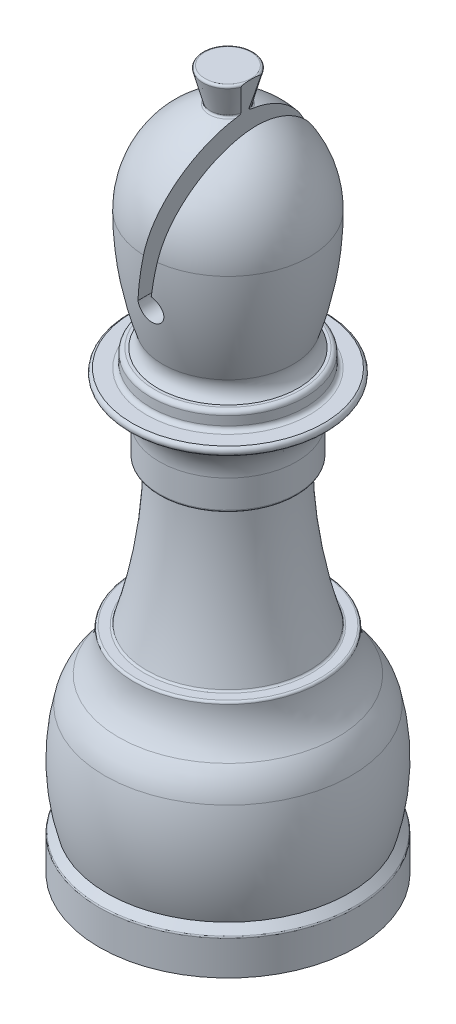
SolidWorks part; units mm, degrees
ref_plane "Front Plane" through (0, 0, 0) normal (0, 0, 1) x (1, 0, 0)
ref_plane "Top Plane" through (0, 0, 0) normal (0, 1, 0) x (1, 0, 0)
ref_plane "Right Plane" through (0, 0, 0) normal (1, 0, 0) x (0, 0, -1)
sketch "Sketch1" plane through (0, 0, 0) normal (0, 0, 1) x (1, 0, 0)
  line L0 (0, 81.5) -> (-2.6742, 81.5)
  line L1 (-15, 4) -> (-15, 0)
  line L2 (-14.1036, 5) -> (-14.9268, 4.1768)
  line L3 (-2.0398, 77.9166) -> (-2.9157, 81.1853)
  line L4 (-9, 51.4698) -> (-9, 52.5)
  line L5 (-8, 42.25) -> (-8, 45.5)
  line L6 (0, 81.5) -> (0, 0)
  line L7 (0, 0) -> (-15, 0)
  line L8 (-8.5, 53) -> (-8.1771, 53)
  line L9 (-9.5, 50.9698) -> (-11.1711, 50.9698)
  line L10 (-7.25, 42) -> (-7.75, 42)
  line L11 (-9.7092, 25) -> (-10.7092, 25)
  line L12 (0, 0) -> (0, -6.9862) construction
  line L13 (-2.9157, 81.1853) -> (-3, 81.5) construction
  line L14 (-3, 81.5) -> (-2.6742, 81.5) construction
  line L15 (-10.9592, 24.75) -> (-10.9592, 25.4702) construction
  arc A0 (-14.9268, 4.1768) -> (-15, 4) centre (-14.75, 4) ccw
  arc A1 (-14.3628, 16.9916) -> (-14.1036, 5) centre (9, 11.4981) ccw
  arc A3 (-10.7092, 25) -> (-10.9592, 24.75) centre (-10.7092, 24.75) ccw
  arc A4 (-9.7092, 25) -> (-9.4697, 25.1781) centre (-9.7092, 25.25) ccw
  arc A5 (-2.6742, 81.5) -> (-2.9157, 81.1853) centre (-2.6742, 81.25) ccw
  arc A6 (-2.1902, 77.6191) -> (-2.0398, 77.9166) centre (-2.2813, 77.8519) ccw
  arc A7 (-2.1902, 77.6191) -> (-9.5, 66.9097) centre (2, 66.9097) ccw
  arc A8 (-9.5, 66.9097) -> (-7.6013, 55.1283) centre (28, 66.9097) ccw
  arc A9 (-8.1771, 53) -> (-7.6013, 55.1283) centre (-9.5, 54.5) ccw
  arc A10 (-8.5, 53) -> (-9, 52.5) centre (-8.5, 52.5) ccw
  arc A11 (-9.5, 50.9698) -> (-9, 51.4698) centre (-9.5, 51.4698) ccw
  arc A12 (-11.1711, 50.9698) -> (-11.1711, 50.0302) centre (-11, 50.5) ccw
  arc A13 (-8, 45.5) -> (-11.1711, 50.0302) centre (-12.8214, 45.5) ccw
  arc A14 (-8, 42.25) -> (-7.75, 42) centre (-7.75, 42.25) ccw
  arc A15 (-7, 41.7489) -> (-7.25, 42) centre (-7.25, 41.75) ccw
  arc A16 (-9.4697, 25.1781) -> (-7, 41.7489) centre (-65.5114, 42) ccw
  arc A17 (-12.7539, 20.0697) -> (-10.9592, 24.75) centre (-17.9592, 24.75) ccw
  arc A18 (-12.7539, 20.0697) -> (-14.3628, 16.9916) centre (-7.5487, 15.3893) ccw
  dimension "D3" = 0.25
  dimension "D4" = 25
  dimension "D5" = 1
  dimension "D6" = 11.5
  dimension "D7" = 37.5
  dimension "D8" = 2
  dimension "D9" = 0.5
  dimension "D10" = 0.5
  dimension "D11" = 3
  dimension "D12" = 42
  dimension "D17" = 9.5
  dimension "D25" = 15
  dimension "D27" = 24
  dimension "D31" = 7
  dimension "D16" = 7
  dimension "D2" = 81.5
  dimension "D13" = 15
  dimension "D14" = 28
  dimension "D15" = 0.5
  dimension "D18" = 42
  dimension "D19" = 8
  dimension "D20" = 50.5
  dimension "D21" = 9
  dimension "D22" = 53
  dimension "D23" = 54.5
  dimension "D24" = 2
  dimension "D26" = 3
  dimension "D28" = 5
  dimension "D29" = 45.5
  dimension "D30" = 135
  dimension "D32" = 4
revolve "Revolve1" add sketch "Sketch1" angle 360 about L12
sketch "Sketch2" plane through (0, 0, 0) normal (0, 0, 1) x (1, 0, 0)
  line L0 (0.9164, 65.6538) -> (0.3439, 62.9601)
  line L1 (-1.5, 61.5) -> (-0.5901, 65.7807)
  line L2 (3.3474, 77.0908) -> (0.9164, 65.6538)
  line L3 (-0.5901, 65.7807) -> (1.9459, 77.7115)
  line L4 (1.9459, 77.7115) -> (2.7775, 81.6241)
  line L5 (2.7775, 81.6241) -> (4.2447, 81.3123)
  line L6 (4.2447, 81.3123) -> (3.3474, 77.0908)
  line L7 (0, 61.1245) -> (0, 78.4799) construction
  line L8 (0, 61.5) -> (0, 81.5) construction
  line L9 (0, 61.5) -> (0, 0) construction
  arc A0 (-1.5, 61.5) -> (0.3439, 62.9601) centre (0, 61.5) ccw
  arc A1 (9.5, 66.9097) -> (2.1902, 77.6191) centre (-2, 66.9097) ccw construction
  point P6 (0, 81.5)
  dimension "D2" = 1.5
  dimension "D1" = 12
  dimension "D3" = 20
  dimension "D4" = 1.5
  dimension "D5" = 61.5
  dimension "D6" = 4
extrude "Cut-Extrude1" cut sketch "Sketch2" against normal through all both and the other way through all
scale "Scale1" scale about origin uniform scaling yes scale factor 0.766667
sketch "Sketch3" plane through (0, 0, 0) normal (0, -1, 0) x (1, 0, 0)
  circle A0 centre (0, 0) radius 10.2
  dimension "D1" = 20.4
extrude "Cut-Extrude2" cut sketch "Sketch3" against normal blind 11 and the other way through all
sketch "Sketch4" plane through (0, 0, 0) normal (0, -1, 0) x (1, 0, 0)
  circle A0 centre (0, 0) radius 9.15
  circle A1 centre (0, 0) radius 10.2 construction
  circle A2 centre (0, 0) radius 10.2
  dimension "D1" = 18.3
sketch "Sketch5" plane through (0, 0, 0) normal (0, 0, 1) x (1, 0, 0)
  line L0 (10.8127, 3.8333) -> (10.8127, 14.5602) construction
  line L1 (10.8127, 3.8333) -> (-10.8127, 3.8333) construction
sketch "Sketch6" plane through (0, 0, 0) normal (0, 0, 1) x (1, 0, 0)
  line L0 (-10.75, 1) -> (0, 1)
  line L1 (-10.75, 1) -> (-10.75, 0)
  line L2 (-10.75, 0) -> (0, 0)
  line L3 (0, 0) -> (0, -1) construction
  line L4 (0, 0) -> (0, 1)
  point P0 (5.375, 0.75)
  point P4 (-6.925, 0)
  dimension "D1" = 12.3
  dimension "D2" = 1
  dimension "D3" = 3.825
  dimension "D4" = 21.5
revolve "Cut-Revolve1" cut sketch "Sketch6" angle 360 about L3
sketch "Sketch7" plane through (0, 0, 0) normal (0, 0, 1) x (1, 0, 0)
  line L0 (0, 0) -> (0, -0.9422) construction
  line L1 (0, 1.0046) -> (0, 3.5)
  line L2 (0, 3.5) -> (-10, 3.5)
  line L3 (-10.55, 0) -> (0, 0)
  line L4 (-10.55, 1) -> (-10.55, 0)
  line L5 (-10, 1) -> (-10.55, 1)
  line L6 (0, 0) -> (0, 1.0046)
  line L7 (-10, 1) -> (-10, 3.5)
  line L8 (-10.75, 0) -> (10.75, 0) construction
  dimension "D1" = 3.5
  dimension "D2" = 20
  dimension "D3" = 21.1
  dimension "D4" = 1
revolve "Base (Black Bishop)" add sketch "Sketch7" angle 360 about L0
sketch "Sketch8" [suppressed] plane through (0, 0, 0) normal (0, 0, 1) x (1, 0, 0)
  line L0 (0, 0) -> (0, -2.2211) construction
  line L1 (0, 0) -> (0, 4.5)
  line L2 (0, 4.5) -> (-10, 4.5)
  line L3 (-10.55, 0) -> (0, 0)
  line L4 (-10.55, 1) -> (-10.55, 0)
  line L5 (-10, 1) -> (-10.55, 1)
  line L7 (-10, 1) -> (-10, 4.5)
  dimension "D2" = 20
  dimension "D3" = 1
  dimension "D4" = 21.1
  dimension "D1" = 4.5
revolve "Base (White Bishop)" [suppressed] add sketch "Sketch8" angle 360 about L0
equation "\"D1@Sketch3\"=20.4mm"
equation "\"D1@Cut-Extrude2\"=5mm + 6mm"
equation "\"D1@Sketch4\"=\"WeightOuterDiam\"+0.3mm"
equation "\"D1\"= \"WeightHeight\""
equation "\"D1@Cut-Extrude3\"=\"QueenHeight\"+\"MagThickness\"-\"FeltThickness\""
equation "\"D1@Sketch2\"=\"MagDiam\""
equation "\"D1@Cut-Extrude1\"=\"QueenHeight\"+\"MagThickness\""
equation "\"MagDiam\"= 12mm"
equation "\"D1@Sketch6\"=\"MagDiam\"+0.3"
equation "\"D1@Sketch7\"=3.5mm"
equation "\"D1@Cut-Extrude4\"=\"SocketDepth\""
equation "\"D1@Sketch8\"=4.5mm"
equation "\"D1@Cut-Extrude5\"=\"ThreadedDepth\"+3mm"
equation "\"PawnHeight\"= 1mm"
equation "\"MagThickness\"= 3mm"
equation "\"KnightHeight\"= 2.5mm"
equation "\"RookHeight\"= 4mm"
equation "\"BishopHeight\"= 5.5mm"
equation "\"QueenHeight\"= 6.5mm"
equation "\"KingHeight\"= 8mm"
equation "\"WeightOuterDiam\"= 18mm"
equation "\"WeightInnerDiam\"= \"MagDiam\" + 0.3mm"
equation "\"WeightHeight\"= 9mm"
equation "\"BaseOuterDiam\"= 20mm"
equation "\"BaseInnerDiam\"= 12.7mm"
equation "\"FeltThickness\"= 1mm"
equation "\"ThreadedDepth\"= 10mm"
equation "\"TapdrillDiam\"= 4.4mm"
equation "\"SocketDepth\"= 5mm"
equation "\"SocketDiam\"= 8.5mm"
equation "\"D1@Sketch5\"=\"SocketDiam\"+0.3"
equation "\"D1@Cut-Extrude6\"=\"ThreadedDepth\"+3mm"
